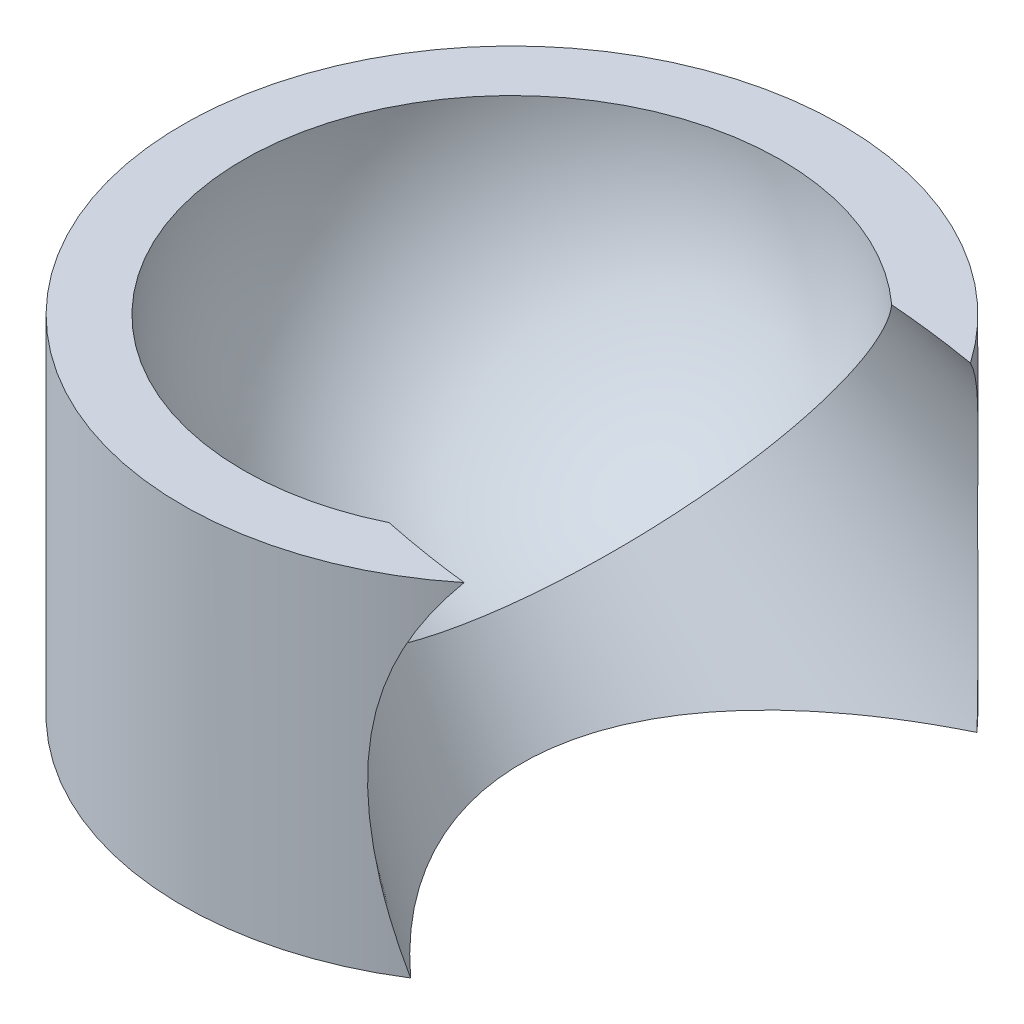
SolidWorks part; units mm, degrees
other "Moving Steel Cup Liner 1"
other "Moving Steel Cup Liner 1 Left"
ref_plane "Front Plane" through (0, 0, 0) normal (0, 0, 1) x (1, 0, 0)
ref_plane "Top Plane" through (0, 0, 0) normal (0, 1, 0) x (1, 0, 0)
ref_plane "Right Plane" through (0, 0, 0) normal (1, 0, 0) x (0, 0, -1)
sketch3d "Keyed Back Sketch datum points"
  point P0 (-56.2917, -97, 0)
  point P1 (-46.2917, -97, 0)
  point P2 (-56.2917, -97, 10)
ref_plane "Keyed Back Sketch plane" through (0, -97, 0) normal (0, -1, 0) x (-1, 0, 0)
sketch "Keyed Back Sketch" plane through (0, -97, 0) normal (0, -1, 0) x (-1, 0, 0)
  line L0 (79.2724, 17.3324) -> (79.2724, 12.6676)
  arc A0 (79.2724, 12.6676) -> (79.2724, 17.3324) centre (82.2724, 15) ccw
extrude "Keyed Back" add sketch "Keyed Back Sketch" along normal blind 0.7 separate body
sketch3d "Cup Blank Sketch datum points"
  point P0 (-56.2917, -97.7, 0)
  point P1 (-46.2917, -97.7, 0)
  point P2 (-56.2917, -97.7, 10)
ref_plane "Cup Blank Sketch plane" through (0, -97.7, 0) normal (0, -1, 0) x (-1, 0, 0)
sketch "Cup Blank Sketch" plane through (0, -97.7, 0) normal (0, -1, 0) x (-1, 0, 0)
  circle A0 centre (82.2724, 15) radius 3.8
extrude "Cup Blank" add sketch "Cup Blank Sketch" along normal blind 3.3
sketch3d "Spherical Bearing Seat axis line"
  line L0 (-82.2724, -101, -25) -> (-82.2724, -101, -5) construction
ref_axis "Spherical Bearing Seat axis" through (-82.2724, -101, -25) along (0, 0, 1)
sketch3d "Spherical Bearing Seat profile datum points"
  point P0 (-82.2724, -101, -15)
  point P1 (-72.2724, -101, -15)
  point P2 (-82.2724, -101, -5)
ref_plane "Spherical Bearing Seat profile plane" through (0, -101, 0) normal (0, -1, 0) x (-1, 0, 0)
sketch "Spherical Bearing Seat profile" plane through (0, -101, 0) normal (0, -1, 0) x (-1, 0, 0)
  line L0 (82.2724, 11.9) -> (82.2724, 18.1)
  arc A0 (82.2724, 18.1) -> (82.2724, 11.9) centre (82.2724, 15) ccw
revolve "Spherical Bearing Seat" cut sketch "Spherical Bearing Seat profile" angle 360 about axis through (-82.2724, -101, -25) along (0, 0, 1)
sketch3d "Articulation Throat axis line"
  line L0 (-90.6158, -106.3831, -16.1872) -> (-73.929, -95.6169, -13.8128) construction
ref_axis "Articulation Throat axis" through (-90.6158, -106.3831, -16.1872) along (0.8343, 0.5383, 0.1187)
sketch3d "Articulation Throat Sketch datum points"
  point P0 (-82.2724, -101, -15)
  point P1 (-82.2724, -98.8462, -24.7653)
  point P2 (-73.929, -95.6169, -13.8128)
ref_plane "Articulation Throat Sketch plane" through (21.8481, -32.2924, -7.1221) normal (0.5512, -0.8148, -0.1797) x (-0.8343, -0.5383, -0.1187)
sketch "Articulation Throat Sketch" plane through (21.8481, -32.2924, -7.1221) normal (0.5512, -0.8148, -0.1797) x (-0.8343, -0.5383, -0.1187)
  line L0 (124.7935, -7.105) -> (124.7935, -4.805)
  line L1 (124.7935, -4.805) -> (101.7935, 1.915)
  line L2 (101.7935, 1.915) -> (101.7935, -7.105)
  line L3 (101.7935, -7.105) -> (124.7935, -7.105)
revolve "Articulation Throat" cut sketch "Articulation Throat Sketch" angle 360 about axis through (-90.6158, -106.3831, -16.1872) along (0.8343, 0.5383, 0.1187)
sketch3d "Mirror1 profile datum points"
  point P0 (0, 0, 0)
  point P1 (10, 0, 0)
  point P2 (0, 0, 10)
ref_plane "Mirror1 profile plane" through (0, 0, 0) normal (0, -1, 0) x (-1, 0, 0)
mirror "Mirror1" about plane through (0, 0, 0) normal (0, -1, 0) of bodies 104
delete or keep bodies "Remove1" type delete bodies bodies 104
